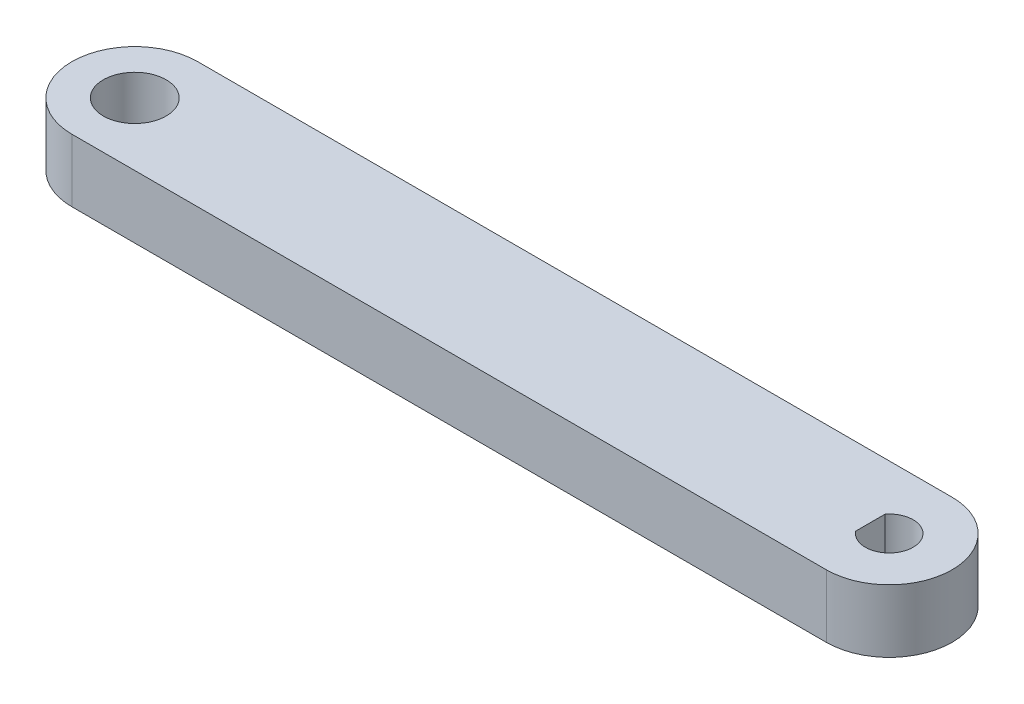
SolidWorks part; units mm, degrees
ref_plane "Front Plane" through (0, 0, 0) normal (0, 0, 1) x (1, 0, 0)
ref_plane "Top Plane" through (0, 0, 0) normal (0, 1, 0) x (1, 0, 0)
ref_plane "Right Plane" through (0, 0, 0) normal (1, 0, 0) x (0, 0, -1)
sketch "Sketch1" plane through (0, 0, 0) normal (0, 1, 0) x (1, 0, 0)
  line L0 (0, 0) -> (-76.2, 0) construction
  line L1 (0, -6.35) -> (-76.2, -6.35)
  line L2 (0, 6.35) -> (-76.2, 6.35)
  arc A0 (0, -6.35) -> (0, 6.35) centre (0, 0) ccw
  arc A1 (-76.2, 6.35) -> (-76.2, -6.35) centre (-76.2, 0) ccw
  point P3 (-38.1, 0)
  dimension "D1" = 6.35
  dimension "D2" = 76.2
extrude "Boss-Extrude1" add sketch "Sketch1" along normal blind 6.35
sketch "Sketch2" plane through (0, 6.35, 0) normal (0, 1, 0) x (1, 0, 0)
  line L0 (-1.905, -1.4811) -> (-1.905, 1.4811)
  circle A0 centre (0, 0) radius 2.413 construction
  arc A1 (-1.905, 1.4811) -> (-1.905, -1.4811) centre (0, 0) cw
  point P5 (2.413, 0)
  dimension "D1" = 4.826
  dimension "D2" = 4.318
extrude "Cut-Extrude1" cut sketch "Sketch2" against normal through all
sketch "Sketch3" plane through (0, 6.35, 0) normal (0, 1, 0) x (1, 0, 0)
  line L0 (-50.8, 2.54) -> (-25.4, 2.54) construction
  line L1 (-38.1, 2.54) -> (-38.1, 6.35) construction
  line L2 (0, 6.35) -> (-76.2, 6.35) construction
  line L3 (-76.2, 6.35) -> (0, 6.35)
  arc A0 (-76.2, 6.35) -> (-76.2, -6.35) centre (-76.2, 0) ccw construction
  arc A1 (0, -6.35) -> (0, 6.35) centre (0, 0) ccw construction
  spline S0 degree 3 poles (-76.2, 6.35) (-67.6435, 6.35) (-51.0509, 1.2887) (-25.1729, 1.2887) (-8.4839, 6.35) (0, 6.35) knots 0 0 0 0 0.334567 0.665433 1 1 1 1
  point P16 (-38.1, 6.35)
  dimension "D1" = 3.81
  dimension "D2" = 25.4
extrude "Cut-Extrude2" [suppressed] cut sketch "Sketch3" against normal through all
mirror "Mirror1" [suppressed] about plane through (0, 0, 0) normal (0, 0, 1)
sketch "Sketch4" plane through (0, 6.35, 0) normal (0, 1, 0) x (1, 0, 0)
  circle A0 centre (-76.2, 0) radius 3.175
  arc A1 (-76.2, 6.35) -> (-76.2, -6.35) centre (-76.2, 0) ccw construction
  dimension "D1" = 6.35
extrude "Cut-Extrude3" cut sketch "Sketch4" against normal through all
